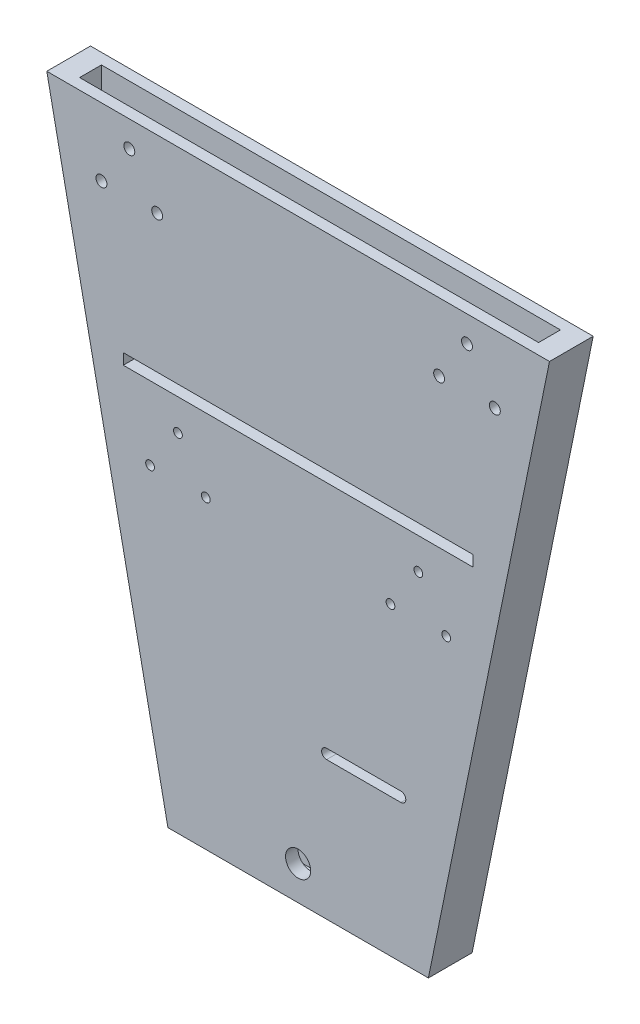
SolidWorks part; units mm, degrees
ref_plane "前视基准面" through (0, 0, 0) normal (0, 0, 1) x (1, 0, 0)
ref_plane "上视基准面" through (0, 0, 0) normal (0, 1, 0) x (1, 0, 0)
ref_plane "右视基准面" through (0, 0, 0) normal (1, 0, 0) x (0, 0, -1)
other "Configuration Table"
sketch "草图1" plane through (0, 0, 0) normal (0, 0, 1) x (1, 0, 0)
  line L0 (0, 0) -> (0, 50.6623) construction
  line L1 (-115, 220) -> (115, 220)
  line L2 (-60, -50) -> (60, -50) construction
  line L3 (-115, 220) -> (-60, -50)
  line L4 (115, 220) -> (60, -50)
  line L5 (-60, -50) -> (-59.5926, -52)
  line L6 (-59.5926, -52) -> (59.5926, -52)
  line L7 (59.5926, -52) -> (60, -50)
  point P6 (0, 220)
  point P7 (0, -50)
  dimension "D1" = 230
  dimension "D2" = 120
  dimension "D3" = 270
  dimension "D4" = 50
  dimension "D5" = 2
extrude "凸台-拉伸1" add sketch "草图1" along normal blind 20
sketch "草图3" plane through (0, 220, 0) normal (0, 1, 0) x (1, 0, 0)
  line L0 (115, -20) -> (-115, -20) construction
  line L1 (-105, -5) -> (105, -5)
  line L2 (-105, -5) -> (-105, -15)
  line L3 (-105, -15) -> (105, -15)
  line L4 (105, -5) -> (105, -15)
  line L5 (-105, -5) -> (105, -15) construction
  line L6 (-105, -15) -> (105, -5) construction
  line L8 (-115, -20) -> (-115, 0) construction
  point P4 (0, -10)
  dimension "D1" = 210
  dimension "D2" = 10
  dimension "D3" = 10
  dimension "D4" = 115
extrude "切除-拉伸1" cut sketch "草图3" against normal blind 15
sketch "草图4" plane through (0, 0, 20) normal (0, 0, 1) x (1, 0, 0)
  line L0 (-96.3631, 128.51) -> (96.3631, 128.51)
  line L1 (-115, 220) -> (-59.5926, -52) construction
  line L2 (59.5926, -52) -> (115, 220) construction
  line L3 (-94.3261, 118.51) -> (94.3261, 118.51)
  line L4 (115, 220) -> (-115, 220) construction
  line L5 (0, 220) -> (0, -87.5938) construction
  line L6 (-80, 126.01) -> (80, 126.01)
  line L7 (-80, 126.01) -> (-80, 121.01)
  line L8 (-80, 121.01) -> (80, 121.01)
  line L9 (80, 126.01) -> (80, 121.01)
  line L10 (-80, 126.01) -> (80, 121.01) construction
  line L11 (-80, 121.01) -> (80, 126.01) construction
  point P14 (0, 123.51)
  dimension "D1" = 10
  dimension "D2" = 91.49
  dimension "D3" = 160
  dimension "D4" = 5
  dimension "D5" = 5
extrude "切除-拉伸2" cut sketch "草图4" against normal blind 10 contours L9 L6 L7 L8
sketch "草图5" plane through (0, 0, 20) normal (0, 0, 1) x (1, 0, 0)
  line L0 (0, 220) -> (0, -61.0662) construction
  line L1 (-96.3631, 128.51) -> (96.3631, 128.51)
  line L2 (-115, 220) -> (-59.5926, -52) construction
  line L3 (59.5926, -52) -> (115, 220) construction
  line L4 (-94.3261, 118.51) -> (94.3261, 118.51)
  line L5 (115, 220) -> (-115, 220) construction
  circle A0 centre (-77.25, 208.1426) radius 2.5
  circle A1 centre (-90, 189) radius 2.5
  circle A2 centre (-64.5, 189) radius 2.5
  circle A3 centre (-55, 106.6526) radius 2
  circle A4 centre (-67.75, 87.51) radius 2
  circle A5 centre (-42.25, 87.51) radius 2
  circle A6 centre (42.25, 87.51) radius 2
  circle A7 centre (67.75, 87.51) radius 2
  circle A8 centre (55, 106.6526) radius 2
  circle A9 centre (64.5, 189) radius 2.5
  circle A10 centre (90, 189) radius 2.5
  circle A11 centre (77.25, 208.1426) radius 2.5
  dimension "D8" = 5
  dimension "D9" = 5
  dimension "D10" = 5
  dimension "D12" = 4
  dimension "D13" = 4
  dimension "D14" = 4
  dimension "D1" = 10
  dimension "D2" = 91.49
  dimension "D3" = 31
  dimension "D4" = 31
  dimension "D5" = 23
  dimension "D6" = 23
  dimension "D7" = 25.5
  dimension "D11" = 90
  dimension "D15" = 23
  dimension "D16" = 23
  dimension "D17" = 31
  dimension "D18" = 31
  dimension "D19" = 25.5
  dimension "D20" = 55
extrude "切除-拉伸3" cut sketch "草图5" against normal blind 10 contours A0 | A2 | A1 | A11 | A10 | A9 | A3 | A5 | A4 | A8 | A6 | A7
ref_plane "基准面1" through (0, 0, 10) normal (0, 0, -1) x (-1, 0, 0)
sketch "草图6" plane through (0, 0, 10) normal (0, 0, -1) x (-1, 0, 0)
  line L0 (0, 220) -> (0, -76.53) construction
  line L1 (0, -49.69) -> (17.4867, -49.69)
  line L2 (-115, 220) -> (115, 220) construction
  line L3 (17.4867, -49.69) -> (12.1089, -23.29)
  line L4 (0, -23.29) -> (12.1089, -23.29)
  line L6 (-59.5926, -52) -> (-115, 220) construction
  arc A0 (0, -23.29) -> (0, -49.69) centre (0, -36.49) ccw
  dimension "D2" = 26.4
  dimension "D1" = 256.49
  dimension "D3" = 14.5
extrude "切除-拉伸4" cut sketch "草图6" against normal mid plane 8.6
sketch "草图7" plane through (0, 0, 0) normal (0, 0, -1) x (-1, 0, 0)
  line L0 (0, 220) -> (0, -74.3263) construction
  line L2 (-115, 220) -> (115, 220) construction
  line L6 (-59.5926, -52) -> (59.5926, -52)
  line L7 (59.5926, -52) -> (115, 220)
  line L8 (-59.5926, -52) -> (59.5926, -52)
  line L9 (-115, 220) -> (-59.5926, -52)
  line L10 (115, 220) -> (-115, 220)
  line L11 (59.5926, -52) -> (115, 220)
  line L13 (-115, 220) -> (-59.5926, -52)
  line L14 (115, 220) -> (-115, 220)
  circle A0 centre (0, -36.49) radius 5.75
  dimension "D2" = 11.5
  dimension "D1" = 256.49
  dimension "D3" = 0
sketch "草图8" plane through (0, 0, 20) normal (0, 0, 1) x (1, 0, 0)
  line L4 (-115, 220) -> (-59.5926, -52)
  line L5 (-59.5926, -52) -> (59.5926, -52)
  line L6 (59.5926, -52) -> (115, 220)
  line L7 (115, 220) -> (-115, 220)
  line L8 (-115, 220) -> (-59.5926, -52)
  line L10 (59.5926, -52) -> (115, 220)
  line L11 (115, 220) -> (-115, 220)
  line L12 (-59.5926, -52) -> (59.5926, -52)
  circle A0 centre (0, -36.49) radius 5.75 construction
  circle A1 centre (0, -36.49) radius 5.75
  circle A2 centre (0, -36.49) radius 5.75
  dimension "D1" = 0
extrude "切除-拉伸6" cut sketch "草图8" against normal blind 15 contours A1
sketch "草图9" plane through (0, 0, 20) normal (0, 0, 1) x (1, 0, 0)
  line L0 (0, 200220) -> (0, -200074.3263) construction
  line L1 (0, 200220) -> (0, -200074.3263) construction
  line L2 (10, 13.51) -> (50, 13.51) construction
  line L3 (10, 17.51) -> (50, 17.51)
  line L4 (-115, 220) -> (-59.5926, -52)
  line L5 (-59.5926, -52) -> (59.5926, -52)
  line L6 (59.5926, -52) -> (115, 220)
  line L7 (115, 220) -> (-115, 220)
  line L8 (-115, 220) -> (-59.5926, -52)
  line L10 (59.5926, -52) -> (115, 220)
  line L11 (115, 220) -> (-115, 220)
  line L12 (10, 9.51) -> (50, 9.51)
  line L13 (-80, 126.01) -> (80, 126.01) construction
  line L14 (18.72, 154.01) -> (18.72, -36.49) construction
  line L15 (-18.72, 154.01) -> (-18.72, -36.49) construction
  line L16 (13, 13.51) -> (47, 13.51) construction
  line L17 (13, 15.76) -> (47, 15.76)
  line L18 (13, 11.26) -> (47, 11.26)
  line L23 (-59.5926, -52) -> (59.5926, -52)
  arc A0 (10, 17.51) -> (10, 9.51) centre (10, 13.51) ccw
  arc A1 (50, 9.51) -> (50, 17.51) centre (50, 13.51) ccw
  circle A2 centre (0, 154.01) radius 18.72 construction
  circle A3 centre (0, -36.49) radius 18.72 construction
  circle A4 centre (10, 13.51) radius 9.185 construction
  arc A5 (13, 15.76) -> (13, 11.26) centre (13, 13.51) ccw
  arc A6 (47, 11.26) -> (47, 15.76) centre (47, 13.51) ccw
  point P8 (30, 13.51)
  point P28 (30, 13.51)
  dimension "D6" = 37.44
  dimension "D7" = 37.44
  dimension "D9" = 18.37
  dimension "D2" = 40
  dimension "D3" = 50
  dimension "D4" = 10
  dimension "D5" = 8
  dimension "D8" = 28
  dimension "D10" = 37.44
  dimension "D11" = 4.5
  dimension "D12" = 3
  dimension "D13" = 3
  dimension "D1" = 0
extrude "切除-拉伸7" cut sketch "草图9" against normal through all contours L18 A6 L17 A5
sketch "草图10" plane through (0, 0, 0) normal (0, 0, -1) x (-1, 0, 0)
  line L2 (-10, 17.51) -> (-50, 17.51)
  line L3 (-50, 9.51) -> (-10, 9.51)
  line L4 (59.5926, -52) -> (115, 220)
  line L5 (-59.5926, -52) -> (59.5926, -52)
  line L6 (-115, 220) -> (-59.5926, -52)
  line L7 (115, 220) -> (-115, 220)
  line L8 (59.5926, -52) -> (115, 220)
  line L10 (-115, 220) -> (-59.5926, -52)
  line L11 (115, 220) -> (-115, 220)
  line L12 (-10, 17.51) -> (-50, 17.51)
  line L13 (-50, 9.51) -> (-10, 9.51)
  line L14 (-13, 15.76) -> (-47, 15.76)
  line L15 (-47, 11.26) -> (-13, 11.26)
  line L16 (-13, 15.76) -> (-47, 15.76)
  line L17 (-47, 11.26) -> (-13, 11.26)
  line L20 (-59.5926, -52) -> (59.5926, -52)
  arc A2 (-50, 17.51) -> (-50, 9.51) centre (-50, 13.51) ccw
  arc A3 (-10, 9.51) -> (-10, 17.51) centre (-10, 13.51) ccw
  arc A4 (-50, 17.51) -> (-50, 9.51) centre (-50, 13.51) ccw
  arc A5 (-10, 9.51) -> (-10, 17.51) centre (-10, 13.51) ccw
  arc A6 (-47, 15.76) -> (-47, 11.26) centre (-47, 13.51) ccw
  arc A7 (-13, 11.26) -> (-13, 15.76) centre (-13, 13.51) ccw
  arc A8 (-47, 15.76) -> (-47, 11.26) centre (-47, 13.51) ccw
  arc A9 (-13, 11.26) -> (-13, 15.76) centre (-13, 13.51) ccw
  arc M13 (-13, 15.76) -> (-13, 11.26) centre (-13, 13.51) cw
  line M14 (-13, 11.26) -> (-47, 11.26)
  arc M15 (-47, 11.26) -> (-47, 15.76) centre (-47, 13.51) cw
  line M16 (-47, 15.76) -> (-13, 15.76)
  dimension "D1" = 0
  dimension "D2" = 0
  dimension "D3" = 0
extrude "切除-拉伸8" cut sketch "草图10" against normal blind 8 contours L13 A5 L12 A4 M16 M13 M14 M15
sketch "草图14" [suppressed] plane through (0, 0, 20) normal (0, 0, 1) x (1, 0, 0)
  line L0 (10, 13.51) -> (50, 13.51) construction
  line L1 (10, 19.51) -> (50, 19.51)
  line L6 (13, 11.26) -> (47, 11.26)
  line L7 (47, 15.76) -> (13, 15.76)
  line L8 (-115, 220) -> (-60, -50)
  line L9 (115, 220) -> (-115, 220)
  line L10 (60, -50) -> (115, 220)
  line L11 (-60, -50) -> (60, -50)
  line L12 (-115, 220) -> (-60, -50)
  line L13 (115, 220) -> (-115, 220)
  line L14 (60, -50) -> (115, 220)
  line L15 (-60, -50) -> (60, -50)
  line L16 (13, 11.26) -> (47, 11.26)
  line L17 (47, 15.76) -> (13, 15.76)
  line L18 (10, 7.51) -> (50, 7.51)
  line L19 (0, 200220) -> (0, -200074.3263) construction
  arc A0 (10, 19.51) -> (10, 7.51) centre (10, 13.51) ccw
  arc A1 (50, 7.51) -> (50, 19.51) centre (50, 13.51) ccw
  arc A6 (47, 11.26) -> (47, 15.76) centre (47, 13.51) ccw
  arc A7 (13, 15.76) -> (13, 11.26) centre (13, 13.51) ccw
  arc A8 (47, 11.26) -> (47, 15.76) centre (47, 13.51) ccw
  arc A9 (13, 15.76) -> (13, 11.26) centre (13, 13.51) ccw
  point P12 (30, 13.51)
  dimension "D4" = 12
  dimension "D1" = 40
  dimension "D5" = 10
  dimension "D6" = 50
  dimension "D2" = 0
  dimension "D3" = 0
extrude "凸台-拉伸3" [suppressed] add sketch "草图14" along normal blind 17
